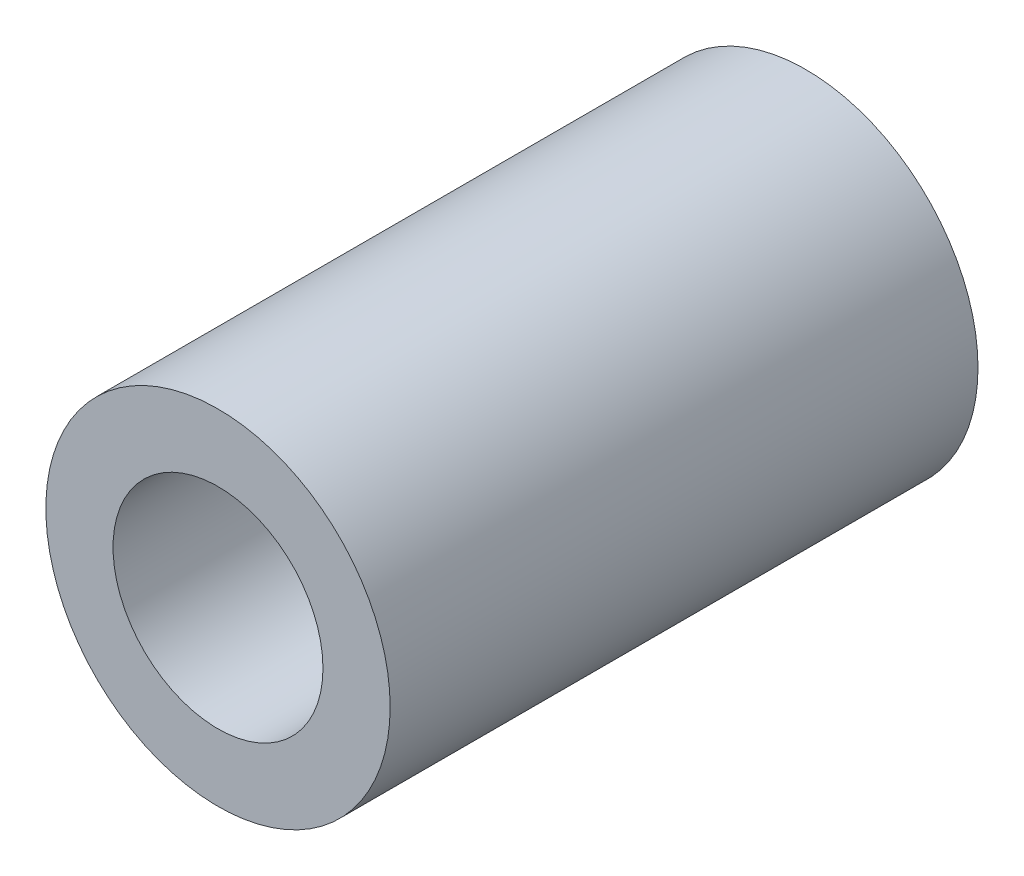
SolidWorks part; units mm, degrees
ref_plane "Front Plane" through (0, 0, 0) normal (0, 0, 1) x (1, 0, 0)
ref_plane "Top Plane" through (0, 0, 0) normal (0, 1, 0) x (1, 0, 0)
ref_plane "Right Plane" through (0, 0, 0) normal (1, 0, 0) x (0, 0, -1)
sketch "Sketch1" plane through (0, 0, 0) normal (0, 0, 1) x (1, 0, 0)
  circle A0 centre (0, 0) radius 12.5
  circle A1 centre (0, 0) radius 20.5
  dimension "D1" = 25
  dimension "D2" = 8
extrude "Boss-Extrude1" add sketch "Sketch1" along normal blind 70
